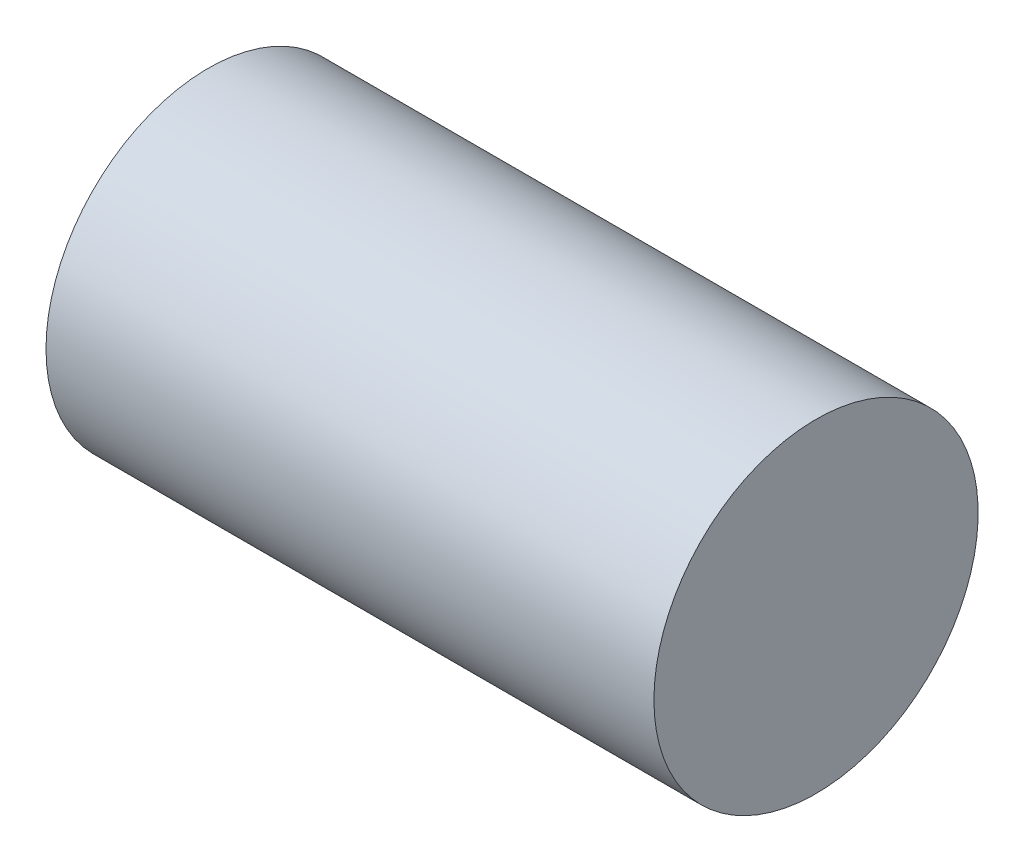
SolidWorks part; units mm, degrees
ref_plane "Front Plane" through (0, 0, 0) normal (0, 0, 1) x (1, 0, 0)
ref_plane "Top Plane" through (0, 0, 0) normal (0, 1, 0) x (1, 0, 0)
ref_plane "Right Plane" through (0, 0, 0) normal (1, 0, 0) x (0, 0, -1)
sketch "Axial blank profile" plane through (0, 0, 0) normal (0, 0, 1) x (1, 0, 0)
  line L0 (-60, 0) -> (30, 0) construction
  line L1 (-41, 0) -> (-11, 0)
  line L2 (-11, 0) -> (-11, 8)
  line L3 (-11, 8) -> (-41, 8)
  line L4 (-41, 8) -> (-41, 0)
revolve "Native revolved blank" add sketch "Axial blank profile" angle 360 about L0
